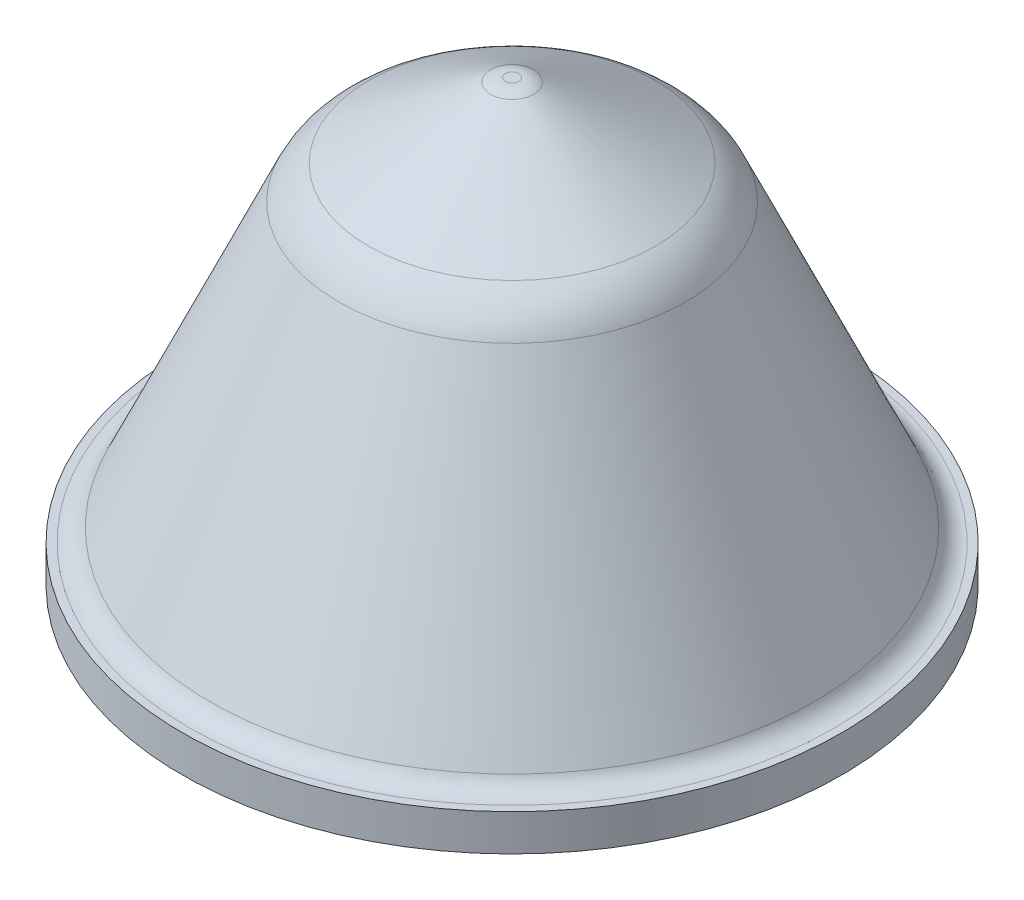
SolidWorks part; units mm, degrees
material "Carburized and nitrided special steel"
ref_plane "Piano frontale" through (0, 0, 0) normal (0, 0, 1) x (1, 0, 0)
ref_plane "Piano superiore" through (0, 0, 0) normal (0, 1, 0) x (1, 0, 0)
ref_plane "Piano destro" through (0, 0, 0) normal (1, 0, 0) x (0, 0, -1)
sketch "Schizzo1" plane through (0, 0, 0) normal (1, 0, 0) x (0, 0, -1)
  line L0 (0, 0) -> (-45, 0)
  line L1 (-45, 0) -> (-45, 5)
  line L2 (-45, 5) -> (-42, 5)
  line L3 (-42, 5) -> (-22.3744, 48.2368)
  line L4 (0, 0) -> (0, 71.1015) construction
  line L5 (0, 60) -> (-2, 60)
  line L6 (0, 0) -> (0, 60)
  line L7 (-2, 60) -> (-22.3744, 48.2368)
  dimension "D1" = 45
  dimension "D2" = 5
  dimension "D3" = 42
  dimension "D4" = 22.3744
  dimension "D5" = 60
  dimension "D6" = 60
  dimension "D8" = 2
revolve "Rivoluzione1" add sketch "Schizzo1" angle 360 about L4
fillet "Raccordo1" radius 3 1 edges at (0, 5, -42)
hole_wizard "Foro filettato M10-1" positions "Schizzo3" profile "Schizzo2" tap size "M10" standard "ISO"
sketch "Schizzo3" plane through (0, 0, 0) normal (0, -1, 0) x (1, 0, 0)
  circle A0 centre (0, 0) radius 45 construction
  point P0 (0, 0)
sketch "Schizzo2" plane through (0, 0, 0) normal (1, 0, 0) x (0, 0, -1)
  line L0 (0, 0) -> (0, 30.0537)
  line L1 (0, 30.0537) -> (4.25, 27.5)
  line L2 (4.25, 27.5) -> (4.25, 0)
  line L5 (4.25, 0) -> (0, 0)
  line L10 (0, 30.0537) -> (-4.25, 27.5) construction
  line L11 (0, -6.35) -> (0, 107.95) construction
  dimension "Tap Drill Dia." = 8.5
  dimension "Tap Drill Depth" = 27.5
  dimension "Drill Angle" = 118
cosmetic thread "Filettatura del foro1" parameters "D1"=20, "D2"=10
fillet "Raccordo2" radius 10 1 edges at (0, 48.2368, -22.3744)
fillet "Raccordo3" radius 4 1 edges at (0, 60, -2)
